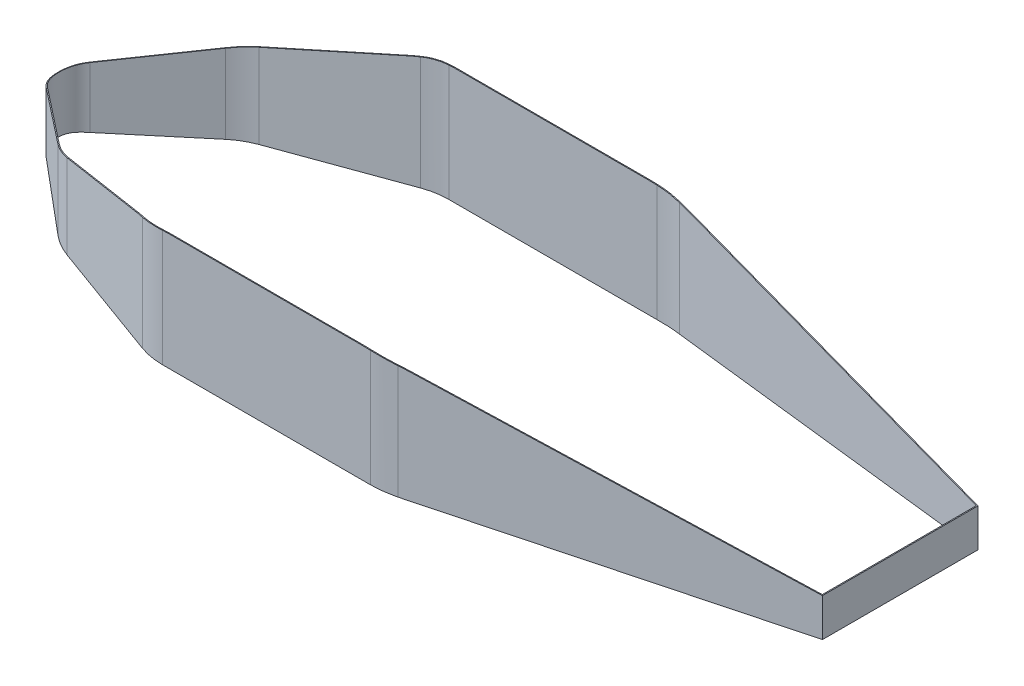
SolidWorks part; units mm, degrees
ref_plane "Front Plane" through (0, 0, 0) normal (0, 0, 1) x (1, 0, 0)
ref_plane "Top Plane" through (0, 0, 0) normal (0, 1, 0) x (1, 0, 0)
ref_plane "Right Plane" through (0, 0, 0) normal (1, 0, 0) x (0, 0, -1)
sketch "Sketch1" plane through (0, 0, 0) normal (0, 1, 0) x (1, 0, 0)
  line L0 (146.0698, 122.5671) -> (556.1483, 466.6637)
  line L1 (676.4552, 536.1229) -> (1335.1737, 775.877)
  line L2 (1471.9818, 800) -> (2631.4601, 800)
  line L3 (2770.3786, 787.8462) -> (4781.451, 433.24)
  line L4 (4781.451, 433.24) -> (4781.451, -433.24)
  line L5 (4781.451, -433.24) -> (2770.3786, -787.8462)
  line L6 (2631.4601, -800) -> (1471.9818, -800)
  line L7 (1335.1737, -775.877) -> (676.4552, -536.1229)
  line L8 (556.1483, -466.6637) -> (146.0698, -122.5671)
  arc A0 (146.0698, 122.5671) -> (146.0698, -122.5671) centre (248.9159, 0) ccw
  arc A1 (676.4552, -536.1229) -> (556.1483, -466.6637) centre (813.2633, -160.2459) cw
  arc A2 (1471.9818, -800) -> (1335.1737, -775.877) centre (1471.9818, -400) cw
  arc A3 (1335.1737, 775.877) -> (1471.9818, 800) centre (1471.9818, 400) cw
  arc A4 (556.1483, 466.6637) -> (676.4552, 536.1229) centre (813.2633, 160.2459) cw
  arc A5 (2770.3786, -787.8462) -> (2631.4601, -800) centre (2631.4601, 0) cw
  arc A6 (2631.4601, 800) -> (2770.3786, 787.8462) centre (2631.4601, 0) cw
  point P12 (0, 0)
  point P15 (610.178, -512)
  point P18 (1401.451, -800)
  point P21 (1401.451, 800)
  point P24 (610.178, 512)
  point P27 (2701.451, -800)
  point P30 (2701.451, 800)
  dimension "r0" = 160
  dimension "r1" = 400
  dimension "r3" = 800
  dimension "x1" = 610.178
  dimension "x2" = 1401.451
  dimension "x3" = 2701.451
  dimension "x4" = 4781.451
  dimension "x6" = 2701.451
  dimension "x7" = 1401.451
  dimension "x8" = 610.178
  dimension "y1" = 512
  dimension "y2" = 800
  dimension "y4" = 433.24
  dimension "y5" = 433.24
  dimension "y6" = 800
  dimension "y8" = 512
extrude "TopView_Extrude" add sketch "Sketch1" along normal blind 800
shell "Shell1" thickness 5
sketch "Sketch2" plane through (0, 0, 0) normal (0, 0, 1) x (1, 0, 0)
  line L0 (0, 300) -> (0, 332.8541)
  line L1 (113.6551, 478.3844) -> (1282.1337, 770.2016)
  line L2 (1524.433, 800) -> (2561.5973, 800)
  line L3 (2839.9436, 780.5361) -> (4781.451, 507.675)
  line L4 (4781.451, 507.675) -> (4781.451, 295.448)
  line L5 (4781.451, 295.448) -> (2805.9583, 157.3079)
  line L6 (2596.6885, 150) -> (150, 150)
  arc A0 (0, 332.8541) -> (113.6551, 478.3844) centre (150, 332.8541) cw
  arc A1 (0, 300) -> (150, 150) centre (150, 300) ccw
  arc A2 (1282.1337, 770.2016) -> (1524.433, 800) centre (1524.433, -200) cw
  arc A3 (2561.5973, 800) -> (2839.9436, 780.5361) centre (2561.5973, -1200) cw
  arc A4 (2805.9583, 157.3079) -> (2596.6885, 150) centre (2596.6885, 3150) cw
  point P10 (0, 450)
  point P13 (0, 150)
  point P16 (1401.451, 800)
  point P19 (2701.451, 800)
  point P22 (2701.451, 150)
  dimension "r0" = 150
  dimension "r2" = 1000
  dimension "r3" = 2000
  dimension "r6" = 3000
  dimension "x2" = 1401.451
  dimension "x3" = 2701.451
  dimension "x4" = 4781.451
  dimension "x6" = 2701.451
  dimension "y0" = 150
  dimension "y1" = 450
  dimension "y2" = 800
  dimension "y4" = 507.675
  dimension "y5" = 295.448
extrude "SideProfile_Cut" cut sketch "Sketch2" against normal through all and the other way through all flip side to cut
